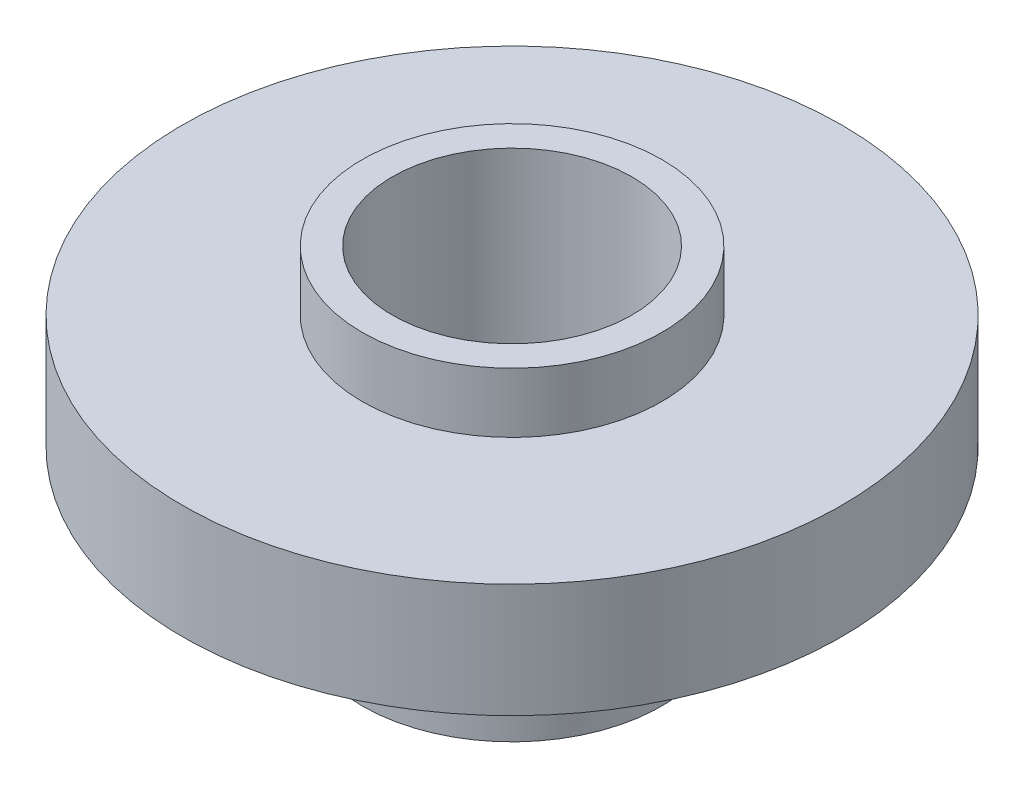
SolidWorks part; units mm, degrees
material "Brass"
ref_plane "Front Plane" through (0, 0, 0) normal (0, 0, 1) x (1, 0, 0)
ref_plane "Top Plane" through (0, 0, 0) normal (0, 1, 0) x (1, 0, 0)
ref_plane "Right Plane" through (0, 0, 0) normal (1, 0, 0) x (0, 0, -1)
sketch "Sketch1" plane through (0, 0, 0) normal (0, 1, 0) x (1, 0, 0)
  circle A0 centre (-3.7324, -0.4934) radius 4
  circle A1 centre (-3.7324, -0.4934) radius 11
  dimension "D1" = 22
  dimension "D2" = 8
extrude "Boss-Extrude1" add sketch "Sketch1" along normal blind 3.8
ref_plane "Plane1" through (0, -5, 0) normal (0, -1, 0) x (-1, 0, 0)
sketch "Sketch2" plane through (0, -5, 0) normal (0, -1, 0) x (-1, 0, 0)
  circle A0 centre (3.7324, -0.4934) radius 5
  circle A1 centre (3.7324, -0.4934) radius 4
  circle A2 centre (3.7324, -0.4934) radius 4 construction
  dimension "D1" = 10
  dimension "D2" = 8
extrude "Boss-Extrude2" add sketch "Sketch2" against normal blind 10.8
